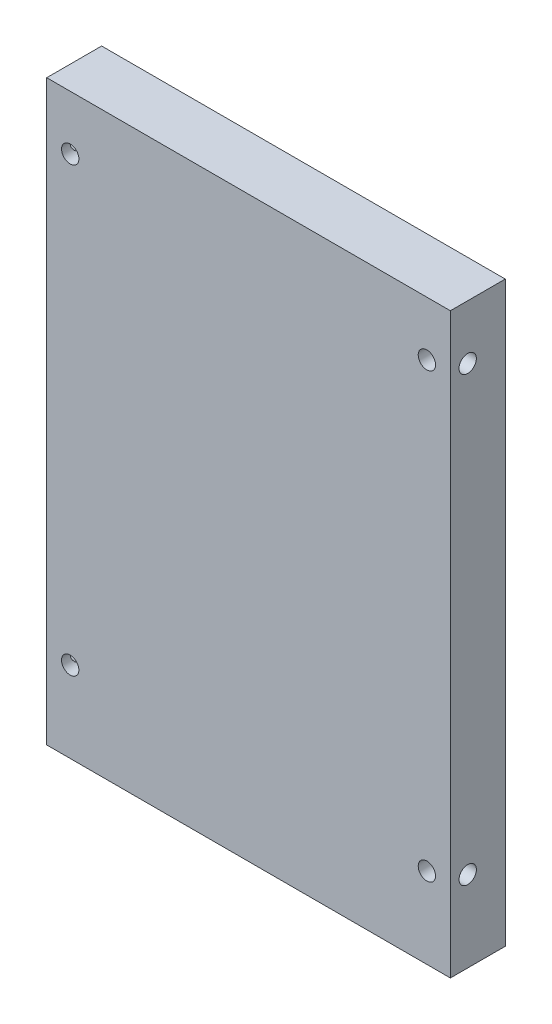
SolidWorks part; units mm, degrees
ref_plane "정면" through (0, 0, 0) normal (0, 0, 1) x (1, 0, 0)
ref_plane "윗면" through (0, 0, 0) normal (0, 1, 0) x (1, 0, 0)
ref_plane "우측면" through (0, 0, 0) normal (1, 0, 0) x (0, 0, -1)
sketch "스케치1" plane through (0, 0, 0) normal (0, 0, 1) x (1, 0, 0)
  line L0 (34.925, 100) -> (34.925, 0) construction
  line L1 (0, 0) -> (69.85, 0)
  line L2 (0, 0) -> (0, 100)
  line L3 (0, 100) -> (69.85, 100)
  line L4 (69.85, 0) -> (69.85, 100)
  line L5 (4.065, 90.6) -> (65.785, 90.6) construction
  line L6 (4.065, 90.6) -> (4.065, 14) construction
  line L7 (4.065, 14) -> (65.785, 14) construction
  line L8 (65.785, 90.6) -> (65.785, 14) construction
  circle A0 centre (4.065, 90.6) radius 1.5
  circle A1 centre (65.785, 90.6) radius 1.5
  circle A2 centre (4.065, 14) radius 1.5
  circle A3 centre (65.785, 14) radius 1.5
  point P11 (34.925, 90.6)
  dimension "D6" = 3
  dimension "D1" = 69.85
  dimension "D2" = 100
  dimension "D3" = 76.6
  dimension "D4" = 14
  dimension "D5" = 61.72
extrude "보스-돌출1" add sketch "스케치1" along normal blind 9.5 contours L3 L4 L1 L2
sketch "스케치2" plane through (69.85, 0, 0) normal (1, 0, 0) x (0, 0, -1)
  line L0 (-6.5, 100) -> (-6.5, 0) construction
  line L1 (-9.5, 100) -> (0, 100) construction
  line L2 (-9.5, 0) -> (0, 0) construction
  line L3 (0, 50) -> (-9.5, 50) construction
  line L4 (0, 0) -> (0, 100) construction
  line L5 (-9.5, 0) -> (-9.5, 100) construction
  line L6 (-9.5, 0) -> (-9.5, 100) construction
  line L7 (-9.5, 0) -> (0, 0) construction
  circle A0 centre (-6.5, 90.6) radius 1.5
  circle A1 centre (-6.5, 14) radius 1.5
  dimension "D1" = 3
  dimension "D4" = 14
  dimension "D2" = 76.6
  dimension "D3" = 3
extrude "컷-돌출1" cut sketch "스케치2" against normal blind 3
ref_plane "평면1" through (34.925, 0, 0) normal (1, 0, 0) x (0, 0, -1)
mirror "대칭 복사1" about plane through (34.925, 0, 0) normal (1, 0, 0) of "컷-돌출1"
sketch "스케치4" plane through (0, 0, 9.5) normal (0, 0, 1) x (1, 0, 0)
  line L0 (34.925, 0) -> (34.925, 100) construction
  line L1 (4.065, 14) -> (65.785, 14) construction
  line L2 (4.065, 14) -> (4.065, 90.6) construction
  line L3 (4.065, 90.6) -> (65.785, 90.6) construction
  line L4 (65.785, 14) -> (65.785, 90.6) construction
  line L5 (0, 0) -> (69.85, 0) construction
  line L6 (0, 100) -> (69.85, 100) construction
  circle A0 centre (4.065, 90.6) radius 1.5
  circle A1 centre (65.785, 90.6) radius 1.5
  circle A2 centre (4.065, 14) radius 1.5
  circle A3 centre (65.785, 14) radius 1.5
  point P10 (34.925, 90.6)
  dimension "D4" = 3
  dimension "D1" = 76.6
  dimension "D2" = 61.72
  dimension "D3" = 14
extrude "컷-돌출3" cut sketch "스케치4" against normal blind 3
